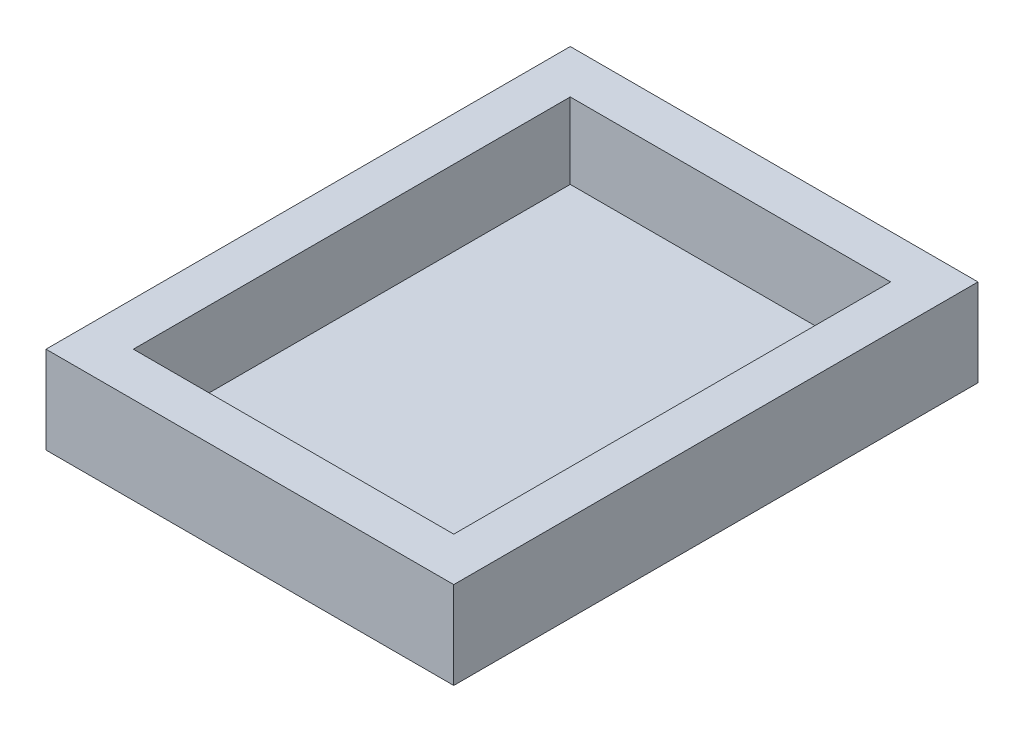
SolidWorks part; units mm, degrees
ref_plane "Front Plane" through (0, 0, 0) normal (0, 0, 1) x (1, 0, 0)
ref_plane "Top Plane" through (0, 0, 0) normal (0, 1, 0) x (1, 0, 0)
ref_plane "Right Plane" through (0, 0, 0) normal (1, 0, 0) x (0, 0, -1)
sketch "Sketch1" plane through (0, 0, 0) normal (0, 1, 0) x (1, 0, 0)
  line L5 (35, -45) -> (-35, -45)
  line L6 (35, -45) -> (35, 45)
  line L7 (35, 45) -> (-35, 45)
  line L8 (-35, -45) -> (-35, 45)
  line L9 (35, -45) -> (-35, 45) construction
  line L10 (35, 45) -> (-35, -45) construction
  point P0 (0, 0)
  dimension "D1" = 90
  dimension "D2" = 70
extrude "Boss-Extrude1" add sketch "Sketch1" along normal blind 15
sketch "Sketch2" plane through (0, 15, 0) normal (0, 1, 0) x (1, 0, 0)
  line L1 (27.5, -37.5) -> (-27.5, -37.5)
  line L2 (27.5, -37.5) -> (27.5, 37.5)
  line L3 (27.5, 37.5) -> (-27.5, 37.5)
  line L4 (-27.5, -37.5) -> (-27.5, 37.5)
  line L5 (27.5, -37.5) -> (-27.5, 37.5) construction
  line L6 (27.5, 37.5) -> (-27.5, -37.5) construction
  point P0 (0, 0)
  dimension "D1" = 75
  dimension "D2" = 55
extrude "Cut-Extrude1" cut sketch "Sketch2" against normal blind 13
